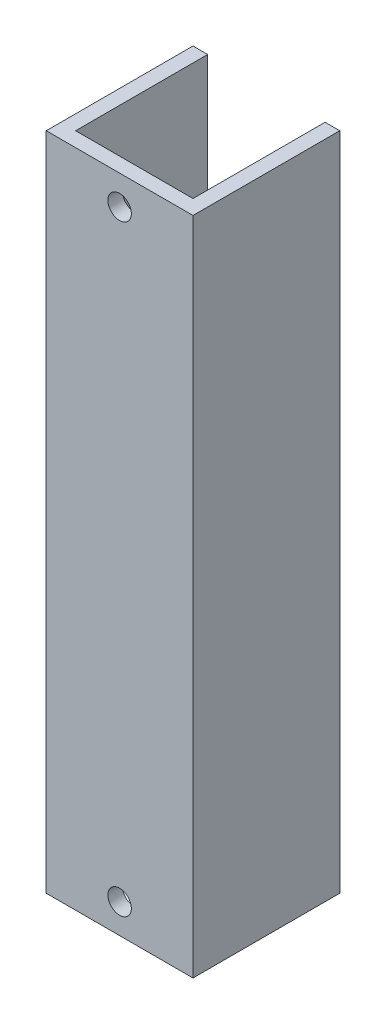
SolidWorks part; units mm, degrees
ref_plane "Front Plane" through (0, 0, 0) normal (0, 0, 1) x (1, 0, 0)
ref_plane "Top Plane" through (0, 0, 0) normal (0, 1, 0) x (1, 0, 0)
ref_plane "Right Plane" through (0, 0, 0) normal (1, 0, 0) x (0, 0, -1)
sketch "Sketch1" plane through (0, 0, 0) normal (0, 1, 0) x (1, 0, 0)
  line L0 (0, 0) -> (31.75, 0)
  line L1 (31.75, 0) -> (31.75, 31.75)
  line L2 (31.75, 31.75) -> (28.575, 31.75)
  line L3 (0, 0) -> (0, 31.75)
  line L4 (0, 31.75) -> (3.175, 31.75)
  line L5 (3.175, 31.75) -> (3.175, 3.175)
  line L6 (3.175, 3.175) -> (28.575, 3.175)
  line L7 (28.575, 3.175) -> (28.575, 31.75)
extrude "Boss-Extrude1" add sketch "Sketch1" along normal blind 142.875
sketch "Sketch3" plane through (0, 0, -3.175) normal (0, 0, -1) x (-1, 0, 0)
  circle A0 centre (-15.875, 6.35) radius 2.54
  circle A1 centre (-15.875, 136.525) radius 2.54
extrude "Cut-Extrude1" cut sketch "Sketch3" against normal blind 3.175
